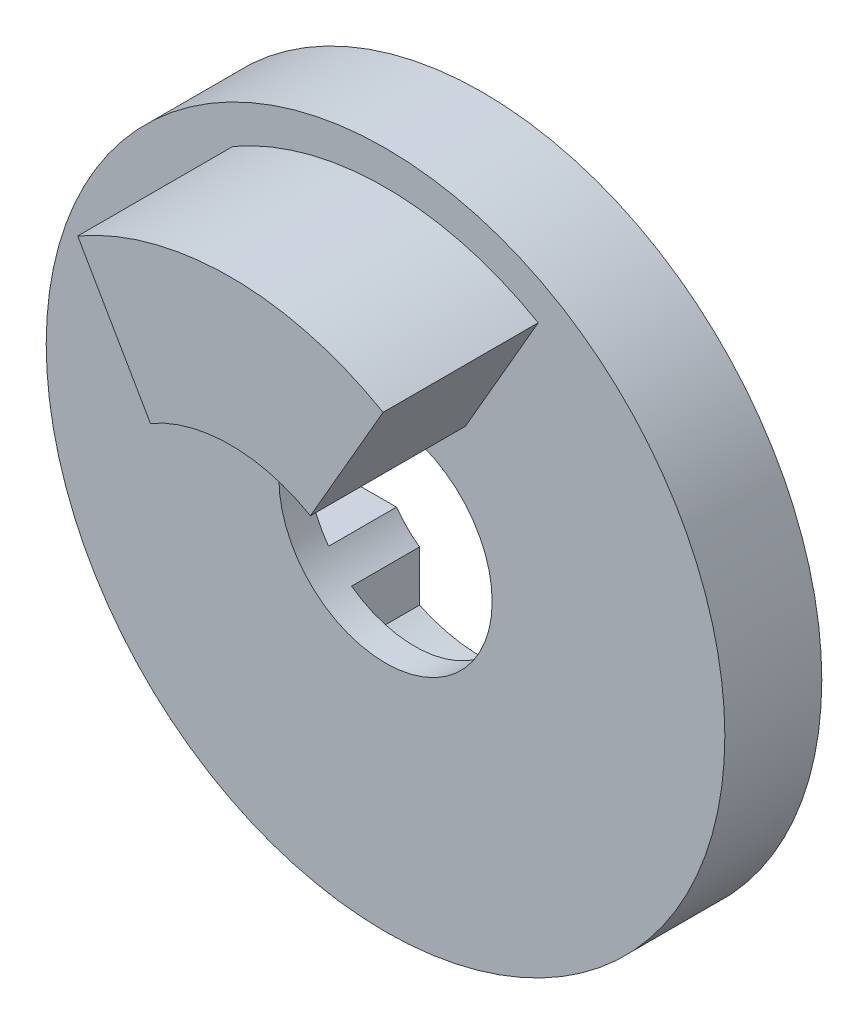
SolidWorks part; units mm, degrees
ref_plane "Front Plane" through (0, 0, 0) normal (0, 0, 1) x (1, 0, 0)
ref_plane "Top Plane" through (0, 0, 0) normal (0, 1, 0) x (1, 0, 0)
ref_plane "Right Plane" through (0, 0, 0) normal (1, 0, 0) x (0, 0, -1)
sketch "Sketch1" plane through (0, 0, 0) normal (0, 0, 1) x (1, 0, 0)
  circle A0 centre (0, 0) radius 17.5
  dimension "D1" = 35
extrude "Boss-Extrude1" add sketch "Sketch1" along normal mid plane 5
sketch "Sketch2" plane through (0, 0, 2.5) normal (0, 0, 1) x (1, 0, 0)
  line L3 (0, 0) -> (0, 11) construction
  line L4 (7.875, 13.6399) -> (4.125, 7.1447)
  line L5 (-4.125, 7.1447) -> (-7.875, 13.6399)
  arc A1 (4.125, 7.1447) -> (-4.125, 7.1447) centre (0, 0) ccw
  arc A6 (-7.875, 13.6399) -> (7.875, 13.6399) centre (0, 0) cw
  circle A7 centre (0, 0) radius 17.5 construction
  dimension "D2" = 7.5
  dimension "D3" = 1.75
  dimension "D1" = 30
extrude "Boss-Extrude2" add sketch "Sketch2" along normal blind 8
sketch "Sketch3" plane through (0, 0, 2.5) normal (0, 0, 1) x (1, 0, 0)
  circle A0 centre (0, 0) radius 5.5
  dimension "D1" = 11
extrude "Cut-Extrude1" cut sketch "Sketch3" against normal through all both and the other way through all
sketch "Sketch4" plane through (0, 0, -2.5) normal (0, 0, -1) x (-1, 0, 0)
  line L0 (-3.25, 7.0356) -> (-3.25, 4.4371)
  line L1 (3.25, 4.4371) -> (3.25, 7.0356)
  line L2 (0, 7.75) -> (0, 5.5) construction
  line L3 (0, 0) -> (2.8238, 0) construction
  line L4 (0, -7.75) -> (0, -5.5) construction
  line L5 (3.25, -4.4371) -> (3.25, -7.0356)
  line L6 (-3.25, -7.0356) -> (-3.25, -4.4371)
  line L7 (-4.4371, 3.25) -> (-7.0356, 3.25)
  line L8 (-7.0356, -3.25) -> (-4.4371, -3.25)
  line L9 (0, 0) -> (0, 2.5464) construction
  line L10 (7.0356, -3.25) -> (4.4371, -3.25)
  line L11 (4.4371, 3.25) -> (7.0356, 3.25)
  circle A0 centre (0, 0) radius 7.75 construction
  arc A1 (-3.25, 7.0356) -> (3.25, 7.0356) centre (0, 0) cw
  circle A2 centre (0, 0) radius 5.5 construction
  arc A3 (-3.25, 4.4371) -> (3.25, 4.4371) centre (0, 0) cw
  arc A4 (-3.25, -4.4371) -> (3.25, -4.4371) centre (0, 0) ccw
  arc A5 (-3.25, -7.0356) -> (3.25, -7.0356) centre (0, 0) ccw
  arc A6 (-4.4371, 3.25) -> (-4.4371, -3.25) centre (0, 0) ccw
  arc A7 (-7.0356, 3.25) -> (-7.0356, -3.25) centre (0, 0) ccw
  arc A8 (7.0356, 3.25) -> (7.0356, -3.25) centre (0, 0) cw
  arc A9 (4.4371, 3.25) -> (4.4371, -3.25) centre (0, 0) cw
  dimension "D1" = 15.5
  dimension "D2" = 6.5
  dimension "D3" = 6.5
extrude "Cut-Extrude4" cut sketch "Sketch4" against normal blind 3.5
sketch "Sketch5" plane through (0, 0, -2.5) normal (0, 0, -1) x (-1, 0, 0)
  circle A0 centre (0, 0) radius 13
  circle A1 centre (0, 0) radius 8
  dimension "D1" = 16
  dimension "D2" = 26
extrude "Cut-Extrude5" cut sketch "Sketch5" against normal blind 2.2
